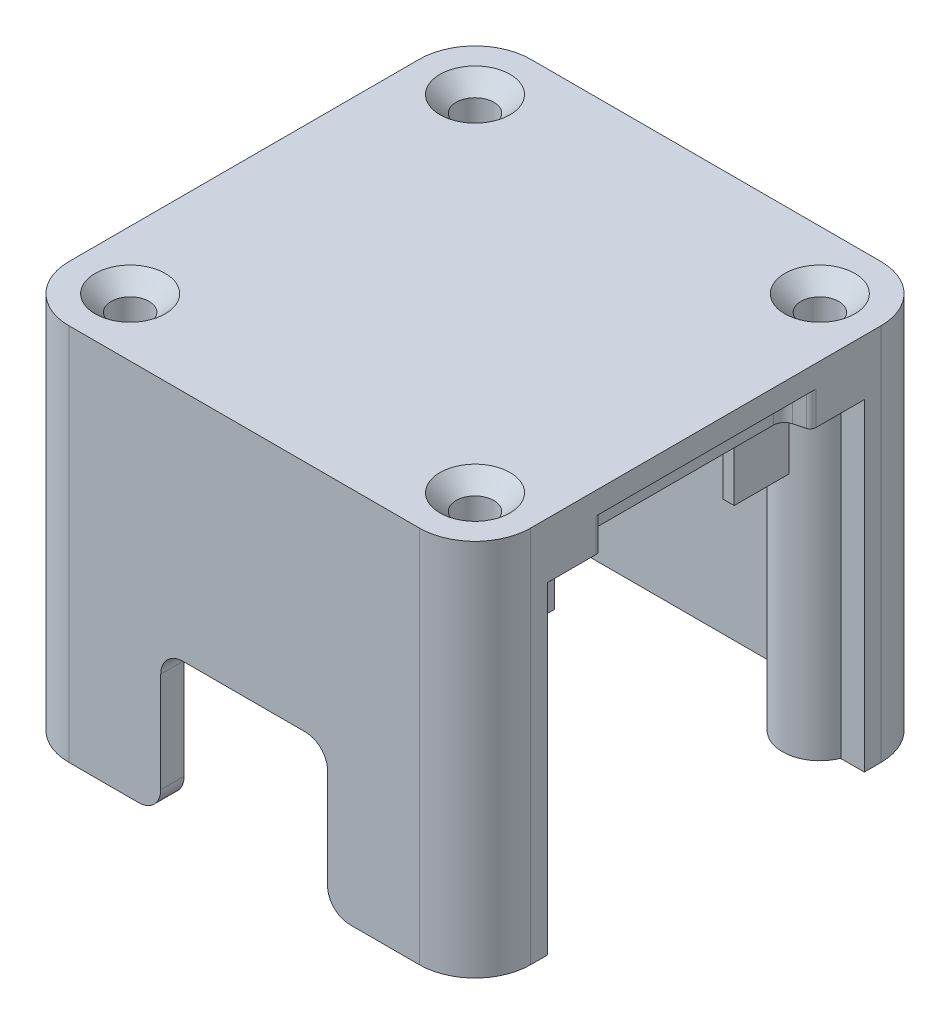
SolidWorks part; units mm, degrees
ref_plane "Front Plane" through (0, 0, 0) normal (0, 0, 1) x (1, 0, 0)
ref_plane "Top Plane" through (0, 0, 0) normal (0, 1, 0) x (1, 0, 0)
ref_plane "Right Plane" through (0, 0, 0) normal (1, 0, 0) x (0, 0, -1)
sketch "Sketch1" plane through (0, 0, 0) normal (0, 1, 0) x (1, 0, 0)
  line L1 (-20.75, 20.75) -> (20.75, 20.75)
  line L2 (-20.75, 20.75) -> (-20.75, -20.75)
  line L3 (-20.75, -20.75) -> (20.75, -20.75)
  line L4 (20.75, 20.75) -> (20.75, -20.75)
  line L5 (-20.75, 20.75) -> (20.75, -20.75) construction
  line L6 (-20.75, -20.75) -> (20.75, 20.75) construction
  point P0 (0, 0)
  dimension "D1" = 41.5
extrude "Boss-Extrude1" add sketch "Sketch1" against normal blind 34
fillet "Fillet1" radius 5 4 edges at (20.75, -17, -20.75) (-20.75, -17, -20.75) (-20.75, -17, 20.75) (20.75, -17, 20.75)
shell "Shell1" thickness 2.1
sketch "Sketch2" plane through (0, 0, 20.75) normal (0, 0, 1) x (1, 0, 0)
  line L0 (-15.75, -34) -> (15.75, -34) construction
  line L1 (-7.5, -34) -> (7.5, -34)
  line L2 (-7.5, -34) -> (-7.5, -21)
  line L3 (-7.5, -21) -> (7.5, -21)
  line L4 (7.5, -34) -> (7.5, -21)
  line L5 (0, 0) -> (0, -21) construction
  dimension "D1" = 15
  dimension "D2" = 13
extrude "Cut-Extrude1" cut sketch "Sketch2" against normal up to next
fillet "Fillet2" radius 2 4 edges at (7.5, -34, 19.7) (7.5, -21, 19.7) (-7.5, -21, 19.7) (-7.5, -34, 19.7)
sketch "Sketch3" plane through (-20.75, 0, 0) normal (-1, 0, 0) x (0, 0, 1)
  line L0 (0, 0) -> (0, -34) construction
  line L1 (-15.75, -34) -> (15.75, -34) construction
  line L2 (8.25, -5) -> (-8.25, -5)
  line L3 (-15.75, 0) -> (15.75, 0) construction
  line L4 (-14.25, -34) -> (-14.25, -26)
  line L5 (-14.25, -26) -> (-8.25, -5)
  line L6 (-14.25, -34) -> (14.25, -34)
  line L7 (14.25, -34) -> (14.25, -26)
  line L8 (14.25, -26) -> (8.25, -5)
  line L9 (14.25, -26) -> (-14.25, -26) construction
  point P8 (0, -5)
  dimension "D1" = 16.5
  dimension "D2" = 5
  dimension "D3" = 28.5
  dimension "D4" = 8
extrude "Cut-Extrude2" cut sketch "Sketch3" against normal up to next
sketch "Sketch4" plane through (20.75, 0, 0) normal (1, 0, 0) x (0, 0, -1)
  line L0 (0, 0) -> (0, -34) construction
  line L1 (-15.75, -34) -> (15.75, -34) construction
  line L2 (-15.75, 0) -> (15.75, 0) construction
  line L3 (-14.25, -5) -> (14.25, -5)
  line L4 (-14.25, -5) -> (-14.25, -34)
  line L5 (-14.25, -34) -> (14.25, -34)
  line L6 (14.25, -5) -> (14.25, -34)
  line L7 (-14.25, -5) -> (14.25, -34) construction
  line L8 (-14.25, -34) -> (14.25, -5) construction
  point P5 (0, -19.5)
  dimension "D1" = 28.5
  dimension "D2" = 5
extrude "Cut-Extrude3" cut sketch "Sketch4" against normal up to next
sketch "Sketch14" plane through (0, -5, 0) normal (0, -1, 0) x (1, 0, 0)
  line L0 (20.75, 9.5) -> (20.75, -9.5)
  line L1 (20.75, -14.25) -> (20.75, 14.25) construction
  line L2 (20.75, -9.5) -> (18.35, -8.8569)
  line L3 (18.35, -8.8569) -> (18.35, 8.8569)
  line L4 (18.35, 8.8569) -> (20.75, 9.5)
  line L5 (18.35, 0) -> (20.75, 0) construction
  dimension "D1" = 19
  dimension "D2" = 2.4
  dimension "D3" = 15
extrude "Cut-Extrude6" cut sketch "Sketch14" against normal blind 3 contours L0 L2 L3 L4
sketch "Sketch6" plane through (0, -5, 0) normal (0, -1, 0) x (1, 0, 0)
  line L1 (18.65, 18.4721) -> (16.75, 18.4721)
  line L2 (18.65, 18.4721) -> (18.65, -18.4721)
  line L3 (18.65, -18.4721) -> (16.75, -18.4721)
  line L4 (16.75, 18.4721) -> (16.75, -18.4721)
  line L5 (18.65, 15.75) -> (18.65, 8.9373) construction
  line L7 (20.75, 9.5) -> (20.75, -9.5) construction
  arc A0 (18.65, 15.75) -> (15.75, 18.65) centre (15.75, 15.75) ccw construction
  arc A1 (15.75, -18.65) -> (18.65, -15.75) centre (15.75, -15.75) ccw construction
  dimension "D1" = 4
extrude "Boss-Extrude2" add sketch "Sketch6" against normal up to surface (2.9 mm away) up to face at (6.1667, -2.1, 0)
sketch "Sketch7" plane through (0, -2.1, 0) normal (0, -1, 0) x (1, 0, 0)
  line L1 (-15.5, 15.5) -> (15.5, 15.5) construction
  line L2 (-15.5, 15.5) -> (-15.5, -15.5) construction
  line L3 (-15.5, -15.5) -> (15.5, -15.5) construction
  line L4 (15.5, 15.5) -> (15.5, -15.5) construction
  line L5 (-15.5, 15.5) -> (15.5, -15.5) construction
  line L6 (-15.5, -15.5) -> (15.5, 15.5) construction
  circle A1 centre (-15.5, 15.5) radius 3.35
  circle A2 centre (15.5, 15.5) radius 3.35
  circle A3 centre (-15.5, -15.5) radius 3.35
  circle A4 centre (15.5, -15.5) radius 3.35
  point P0 (0, 0)
  dimension "D1" = 6.7
  dimension "D2" = 31
extrude "Boss-Extrude3" add sketch "Sketch7" along normal up to surface (31.9 mm away) up to face at (16.367, -34, 17.5545)
sketch "Sketch11" plane through (0, -2.1, 0) normal (0, -1, 0) x (1, 0, 0)
  arc A12 (14.0195, 19.5903) -> (19.5903, 14.0195) centre (15.5, 15.5) ccw
  circle A13 centre (15.5, 15.5) radius 4.35
  arc A15 (-19.5903, 14.0195) -> (-14.0195, 19.5903) centre (-15.5, 15.5) ccw
  circle A16 centre (-15.5, 15.5) radius 4.35
  arc A18 (-14.0195, -19.5903) -> (-19.5903, -14.0195) centre (-15.5, -15.5) ccw
  circle A19 centre (-15.5, -15.5) radius 4.35
  arc A21 (19.5903, -14.0195) -> (14.0195, -19.5903) centre (15.5, -15.5) ccw
  circle A22 centre (15.5, -15.5) radius 4.35
  dimension "D1" = 1
  dimension "D2" = 1
  dimension "D3" = 1
  dimension "D4" = 1
extrude "Boss-Extrude5" add sketch "Sketch11" along normal blind 1
hole_wizard "CSK for M3 Flat Head Machine Screw1" positions "Sketch8" profile "Sketch9" countersink size "M3" standard "ANSI Metric" end condition through all
sketch "Sketch8" plane through (0, 0, 0) normal (0, 1, 0) x (1, 0, 0)
  point P0 (-15.5, -15.5)
  point P2 (-15.5, 15.5)
  point P9 (15.5, -15.5)
  point P12 (15.5, 15.5)
sketch "Sketch9" plane through (-15.5, 0, 15.5) normal (1, 0, 0) x (0, 0, 1)
  line L0 (0, 0) -> (0, 34)
  line L1 (0, 34) -> (1.7, 34)
  line L2 (1.7, 34) -> (1.7, 1.45)
  line L3 (1.7, 1.45) -> (3.15, 0)
  line L5 (3.15, 0) -> (0, 0)
  line L6 (-1.7, 1.45) -> (-3.15, 0) construction
  line L11 (0, -6.35) -> (0, 107.95) construction
  dimension "Thru Hole Dia." = 3.4
  dimension "Thru Hole Depth" = 34
  dimension "Near C'Sink Dia." = 6.3
  dimension "Near C'Sink Angle" = 90
sketch "Sketch10" plane through (0, -2.1, 0) normal (0, -1, 0) x (1, 0, 0)
  line L0 (0, 0) -> (6.75, 0) construction
  line L1 (6.75, 7.575) -> (6.75, -7.575) construction
  line L4 (20.75, 9.5) -> (20.75, 14.25) construction
  circle A0 centre (6.75, 7.575) radius 1.325
  circle A1 centre (6.75, 7.575) radius 3
  circle A2 centre (6.75, -7.575) radius 3
  circle A3 centre (6.75, -7.575) radius 1.325
  dimension "D1" = 12.5
  dimension "D2" = 2.65
  dimension "D3" = 6
  dimension "D4" = 11
extrude "Boss-Extrude4" add sketch "Sketch10" along normal blind 10
sketch "Sketch13" plane through (0, -12.1, 0) normal (0, -1, 0) x (1, 0, 0)
  line L1 (5.0187, 5.125) -> (8.4813, 5.125)
  line L2 (5.0187, 5.125) -> (5.0187, -5.125)
  line L3 (5.0187, -5.125) -> (8.4813, -5.125)
  line L4 (8.4813, 5.125) -> (8.4813, -5.125)
  circle A0 centre (6.75, 7.575) radius 3 construction
  circle A1 centre (6.75, -7.575) radius 3 construction
  circle A2 centre (6.75, -7.575) radius 3 construction
  dimension "D1" = 10.25
extrude "Cut-Extrude5" cut sketch "Sketch13" against normal up to surface (10 mm away) up to face at (6.75, -2.1, -4.575)
sketch "Sketch12" plane through (0, -2.1, 0) normal (0, -1, 0) x (1, 0, 0)
  line L0 (-18.65, 0) -> (16.75, 0)
  line L1 (-18.65, -12.5) -> (-18.65, 12.5) construction
  line L2 (16.75, 12.3919) -> (16.75, -12.3919) construction
  line L3 (-18.65, 7.575) -> (5.425, 7.575)
  line L4 (-18.65, -8.25) -> (-18.65, 8.25) construction
  line L5 (-18.65, -7.575) -> (5.425, -7.575)
  line L6 (5.425, 7.575) -> (6.75, 7.575) construction
  line L7 (5.425, -7.575) -> (6.75, -7.575) construction
  line L8 (0, -18.65) -> (0, 18.65)
  line L9 (14.3598, -18.65) -> (-14.3598, -18.65) construction
  line L10 (-12.5, 18.65) -> (12.5, 18.65) construction
  line L11 (-9.25, 18.65) -> (-9.25, -18.65)
  line L12 (-5.5, 18.65) -> (5.5, 18.65) construction
  line L13 (9.25, 18.65) -> (9.25, -18.65)
  line L14 (12.5, -18.65) -> (-12.5, -18.65) construction
  line L15 (0, 18.65) -> (0, 25.9199) construction
  arc A0 (8.4813, 5.125) -> (5.0187, 5.125) centre (6.75, 7.575) ccw construction
  circle A4 centre (6.75, 7.575) radius 1.325 construction
  circle A5 centre (6.75, 7.575) radius 1.325 construction
  circle A6 centre (6.75, -7.575) radius 1.325 construction
  circle A7 centre (6.75, -7.575) radius 1.325 construction
  dimension "D1" = 0.5
extrude "Extrude-Thin4" add sketch "Sketch12" against normal up to surface (2.9 mm away) thin
fillet "Fillet3" radius 1 2 edges at (18.65, -3.55, -8.9373) (18.65, -3.55, 8.9373)
fillet "Fillet4" radius 0.5 2 edges at (20.75, -3.5, -9.5) (20.75, -3.5, 9.5)
sketch "Sketch15" plane through (0, -2.1, 0) normal (0, -1, 0) x (1, 0, 0)
  line L0 (16.05, 8.9) -> (16.05, 12.1955)
  line L1 (16.05, -12.1955) -> (16.05, -7.25)
  line L2 (9.5, 20.75) -> (15.75, 20.75) construction
  line L4 (20.75, 9.8837) -> (20.75, 14.25) construction
  line L5 (15.75, -20.75) -> (-15.75, -20.75) construction
  line L6 (16.05, 12.1955) -> (16.05, 13.0854)
  line L7 (16.05, -12.1955) -> (16.05, -13.059)
  arc A0 (14.3598, 18.65) -> (18.65, 14.3598) centre (15.5, 15.5) ccw construction
  arc A2 (18.65, -14.3598) -> (14.3598, -18.65) centre (15.5, -15.5) ccw construction
  dimension "D1" = 11.85
  dimension "D2" = 13.5
  dimension "D3" = 4.7
extrude "Extrude-Thin5" add sketch "Sketch15" along normal blind 10 thin contours L7 L1 thin type one direction reverse wall 1
